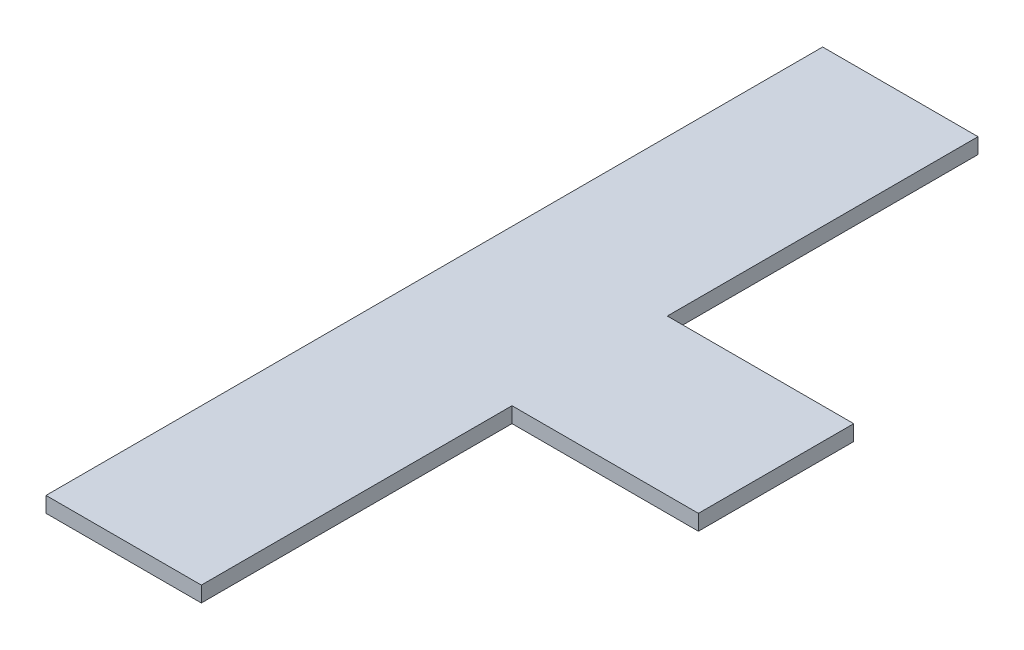
SolidWorks part; units mm, degrees
ref_plane "Front Plane" through (0, 0, 0) normal (0, 0, 1) x (1, 0, 0)
ref_plane "Top Plane" through (0, 0, 0) normal (0, 1, 0) x (1, 0, 0)
ref_plane "Right Plane" through (0, 0, 0) normal (1, 0, 0) x (0, 0, -1)
sketch "Sketch1" plane through (0, 0, 0) normal (0, 1, 0) x (1, 0, 0)
  line L0 (0, 0) -> (0, -50)
  line L1 (0, 0) -> (10, 0)
  line L2 (10, 0) -> (10, -50)
  line L3 (0, -50) -> (10, -50)
  line L4 (10, -20) -> (22, -20)
  line L5 (22, -20) -> (22, -30)
  line L6 (22, -30) -> (10, -30)
  dimension "D1" = 50
  dimension "D2" = 10
  dimension "D3" = 50
  dimension "D4" = 12
  dimension "D5" = 20
  dimension "D6" = 10
extrude "Boss-Extrude1" add sketch "Sketch1" along normal blind 1 contours L0 L3 L2 L1 | L6 L5 L4 L2
